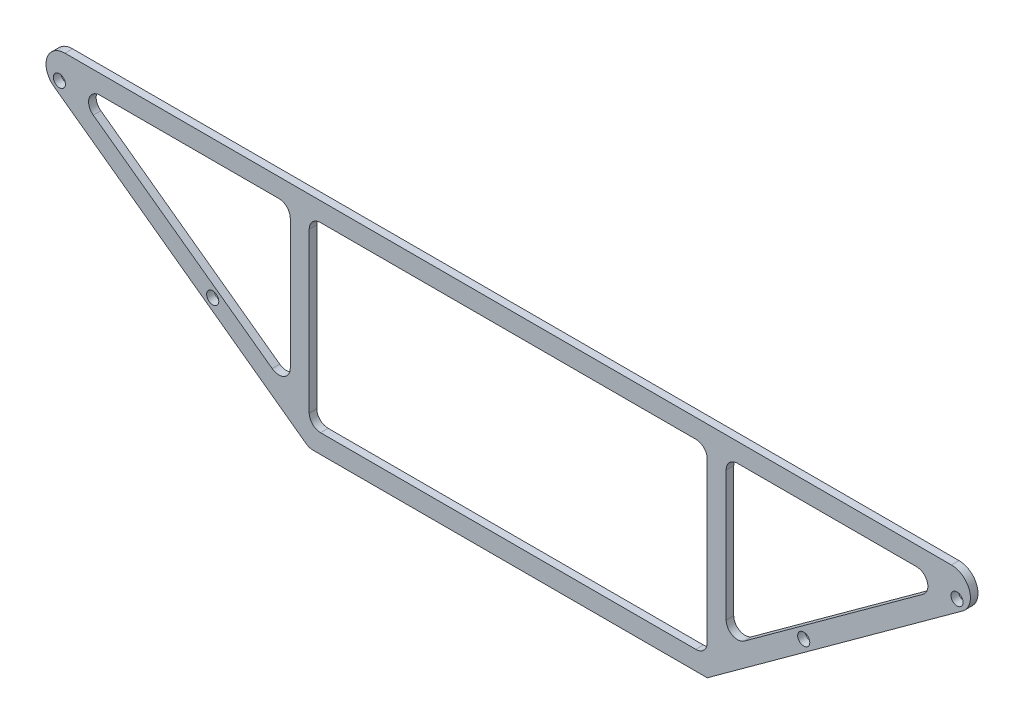
SolidWorks part; units mm, degrees
material "6061 合金"
ref_plane "正面" through (0, 0, 0) normal (0, 0, 1) x (1, 0, 0)
ref_plane "平面" through (0, 0, 0) normal (0, 1, 0) x (1, 0, 0)
ref_plane "右側面" through (0, 0, 0) normal (1, 0, 0) x (0, 0, -1)
sketch "ｽｹｯﾁ1" plane through (0, 0, 0) normal (0, 0, 1) x (1, 0, 0)
  line L0 (-116.9417, 29) -> (116.9417, 29)
  line L1 (52.5, -24) -> (-52.5, -24)
  line L2 (52.5, -24) -> (52.5, 24)
  line L3 (52.5, 24) -> (-52.5, 24)
  line L4 (-52.5, -24) -> (-52.5, 24)
  line L5 (52.5, -24) -> (-52.5, 24) construction
  line L6 (52.5, 24) -> (-52.5, -24) construction
  line L7 (119.8807, 19.9549) -> (52.5, -29)
  line L8 (52.5, -29) -> (-52.5, -29)
  line L9 (-52.5, -29) -> (-119.8807, 19.9549)
  line L10 (-128.0769, 29) -> (-48.2467, -29) construction
  line L11 (0, 29) -> (0, -29) construction
  line L12 (128.0769, 29) -> (48.2467, -29) construction
  line L13 (-116.9417, 24) -> (-119.8807, 19.9549) construction
  line L14 (116.9417, 24) -> (119.8807, 19.9549) construction
  line L15 (-57.5, 21) -> (-57.5, -13.2991)
  line L16 (-62.2634, -15.7262) -> (-116.9417, 24)
  line L17 (-116.9417, 24) -> (-60.5, 24)
  line L18 (62.2634, -15.7262) -> (116.9417, 24)
  line L19 (57.5, 21) -> (57.5, -13.2991)
  line L20 (116.9417, 24) -> (60.5, 24)
  arc A0 (116.9417, 29) -> (119.8807, 19.9549) centre (116.9417, 24) cw
  arc A1 (-116.9417, 29) -> (-119.8807, 19.9549) centre (-116.9417, 24) ccw
  circle A2 centre (118.4112, 21.9775) radius 1.6
  circle A3 centre (77.9603, -7.4118) radius 1.6
  circle A4 centre (-118.4112, 21.9775) radius 1.6
  circle A5 centre (-77.9603, -7.4118) radius 1.6
  arc A6 (-57.5, -13.2991) -> (-62.2634, -15.7262) centre (-60.5, -13.2991) cw
  arc A7 (-57.5, 21) -> (-60.5, 24) centre (-60.5, 21) ccw
  arc A8 (57.5, -13.2991) -> (62.2634, -15.7262) centre (60.5, -13.2991) ccw
  arc A9 (57.5, 21) -> (60.5, 24) centre (60.5, 21) cw
  point P0 (0, 0)
  dimension "D7" = 5
  dimension "D8" = 50
  dimension "D9" = 3.2
  dimension "D12" = 3
  dimension "D1" = 105
  dimension "D2" = 48
  dimension "D3" = 5
  dimension "D4" = 5
  dimension "D5" = 54
  dimension "D6" = 2.5
  dimension "D10" = 5
  dimension "D11" = 5
extrude "ﾎﾞｽ - 押し出し1" add sketch "ｽｹｯﾁ1" along normal blind 2
fillet "ﾌｨﾚｯﾄ1" radius 3 7 edges at (116.9417, 24, 1) (52.5, -24, 1) (52.5, 24, 1) (-52.5, -29, 1) (-52.5, -24, 1) (-52.5, 24, 1) (-116.9417, 24, 1)
